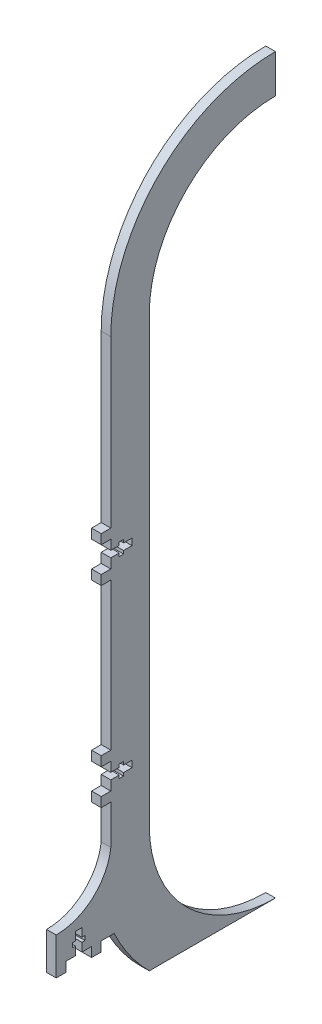
SolidWorks part; units mm, degrees
ref_plane "Front Plane" through (0, 0, 0) normal (0, 0, 1) x (1, 0, 0)
ref_plane "Top Plane" through (0, 0, 0) normal (0, 1, 0) x (1, 0, 0)
ref_plane "Right Plane" through (0, 0, 0) normal (1, 0, 0) x (0, 0, -1)
sketch "Elevator Ball Support Rail" plane through (0, 0, 0) normal (1, 0, 0) x (0, 0, -1)
  line L0 (83.312, 229.362) -> (83.312, 254.762)
  line L1 (-31.75, -120.142) -> (-25.4, -120.142)
  line L2 (83.312, -229.362) -> (0, -229.362)
  line L3 (-31.75, -196.342) -> (-23.2361, -196.342)
  line L6 (0, 146.05) -> (0, -146.05)
  line L7 (-25.4, -146.05) -> (-25.4, -196.342) construction
  line L8 (0, -146.05) -> (0, -229.362) construction
  line L12 (-61.468, -178.0893) -> (-61.468, -196.342)
  line L42 (0, 0) -> (-25.4, 0) construction
  line L46 (-25.4, 6.858) -> (-25.4, -90.424)
  line L47 (-25.4, -90.424) -> (-31.75, -90.424)
  line L48 (-25.4, -96.774) -> (-25.4, -103.124)
  line L49 (-31.75, -90.424) -> (-31.75, -96.774)
  line L50 (-31.75, -96.774) -> (-25.4, -96.774)
  line L51 (-25.4, -103.124) -> (-19.865, -103.124)
  line L52 (-19.865, -103.124) -> (-19.865, -101.083)
  line L53 (-19.865, -101.083) -> (-16.965, -101.083)
  line L54 (-16.965, -101.083) -> (-16.965, -103.124)
  line L55 (-16.965, -103.124) -> (-11.43, -103.124)
  line L56 (-11.43, -103.124) -> (-11.43, -107.442)
  line L57 (-11.43, -107.442) -> (-16.965, -107.442)
  line L58 (-16.965, -107.442) -> (-16.965, -109.483)
  line L59 (-16.965, -109.483) -> (-19.865, -109.483)
  line L60 (-19.865, -109.483) -> (-19.865, -107.442)
  line L61 (-19.865, -107.442) -> (-25.4, -107.442)
  line L62 (-25.4, -107.442) -> (-25.4, -113.792)
  line L63 (-25.4, -113.792) -> (-31.75, -113.792)
  line L64 (-31.75, -113.792) -> (-31.75, -120.142)
  line L66 (-25.4, -120.142) -> (-25.4, -146.05)
  line L68 (-25.4, 36.576) -> (-25.4, 146.05)
  arc A0 (0, 146.05) -> (83.312, 229.362) centre (83.312, 146.05) cw
  arc A1 (83.312, 254.762) -> (-25.4, 146.05) centre (83.312, 146.05) ccw
  arc A2 (0, -146.05) -> (83.312, -229.362) centre (83.312, -146.05) ccw
  arc A3 (-23.2361, -196.342) -> (0, -229.362) centre (83.312, -146.05) ccw
  arc A4 (-61.468, -178.0893) -> (-25.4, -146.05) centre (-61.468, -141.768) ccw
  point P4 (0, 0)
  line B0 (-55.118, -196.342) -> (-55.118, -202.692)
  line B1 (-55.118, -202.692) -> (-61.468, -202.692)
  line B2 (-61.468, -202.692) -> (-61.468, -196.342)
  line B3 (-48.768, -196.342) -> (-48.768, -190.807)
  line B4 (-48.768, -190.807) -> (-50.809, -190.807)
  line B5 (-50.809, -190.807) -> (-50.809, -187.907)
  line B6 (-50.809, -187.907) -> (-48.768, -187.907)
  line B7 (-48.768, -187.907) -> (-48.768, -182.372)
  line B8 (-48.768, -182.372) -> (-44.45, -182.372)
  line B9 (-44.45, -182.372) -> (-44.45, -187.907)
  line B10 (-44.45, -187.907) -> (-42.409, -187.907)
  line B11 (-42.409, -187.907) -> (-42.409, -190.807)
  line B12 (-42.409, -190.807) -> (-44.45, -190.807)
  line B13 (-44.45, -190.807) -> (-44.45, -196.342)
  line B14 (-46.609, -182.372) -> (-46.609, -196.342) construction
  line B15 (-38.1, -196.342) -> (-44.45, -196.342)
  line B16 (-31.75, -202.692) -> (-31.75, -196.342)
  line B17 (-55.118, -196.342) -> (-48.768, -196.342)
  line B18 (-38.1, -202.692) -> (-31.75, -202.692)
  line B19 (-38.1, -196.342) -> (-38.1, -202.692)
  line B20 (-25.4, 30.226) -> (-31.75, 30.226)
  line B21 (-31.75, 30.226) -> (-31.75, 36.576)
  line B22 (-31.75, 36.576) -> (-25.4, 36.576)
  line B23 (-25.4, 23.876) -> (-19.865, 23.876)
  line B24 (-19.865, 23.876) -> (-19.865, 25.917)
  line B25 (-19.865, 25.917) -> (-16.965, 25.917)
  line B26 (-16.965, 25.917) -> (-16.965, 23.876)
  line B27 (-16.965, 23.876) -> (-11.43, 23.876)
  line B28 (-11.43, 23.876) -> (-11.43, 19.558)
  line B29 (-11.43, 19.558) -> (-16.965, 19.558)
  line B30 (-16.965, 19.558) -> (-16.965, 17.517)
  line B31 (-16.965, 17.517) -> (-19.865, 17.517)
  line B32 (-19.865, 17.517) -> (-19.865, 19.558)
  line B33 (-19.865, 19.558) -> (-25.4, 19.558)
  line B34 (-11.43, 21.717) -> (-25.4, 21.717) construction
  line B35 (-25.4, 13.208) -> (-25.4, 19.558)
  line B36 (-31.75, 6.858) -> (-25.4, 6.858)
  line B37 (-25.4, 30.226) -> (-25.4, 23.876)
  line B38 (-31.75, 13.208) -> (-31.75, 6.858)
  line B39 (-25.4, 13.208) -> (-31.75, 13.208)
  dimension "D5" = 25.4
  dimension "D4" = 83.312
  dimension "D7" = 83.312
  dimension "D8" = 26.67
  dimension "D6" = 203.2
  dimension "D1" = 6.35
  dimension "D3" = 292.1
  dimension "D9" = 40.604
  dimension "D20" = 50.292
  dimension "D28" = 6.35
  dimension "D29" = 4.318
  dimension "D30" = 2.9
  dimension "D31" = 13.97
  dimension "D32" = 6.35
  dimension "D33" = 8.4
  dimension "D34" = 6.35
  dimension "D36" = 25.4
  dimension "D37" = 76.2
sketch_block_instance "Male T-slot assembly-1"
sketch_block "Male T-slot assembly" parameters "D1"=6.35, "D2"=6.35, "D3"=4.318, "D4"=2.9, "D5"=8.4, "D6"=13.97, "D7"=6.35
sketch_block_instance "Male T-slot assembly-5"
extrude "Boss-Extrude2" add sketch "Elevator Ball Support Rail" along normal blind 6.35
equation "\"Ball Diameter\"= 1.75in"
equation "\"Pulley Diameter\" = 1in"
equation "\"Reactor Height\" = 14in"
equation "\"Sheet Thickness\"= 0.25in"
equation "\"Screw Diameter\"= .17in"
equation "\"Robot Diameter\"= 14in"
equation "\"Castor Screw Diameter\"= 0.22in"
equation "\"Wheel Diameter\" = 4in"
equation "\"Nut Diameter\" = 8.4mm"
equation "\"Nut Height\" = 2.9mm"
equation "\"Screw Height\" = 0.55in"
equation "\"D11@Elevator Ball Support Rail\"=\"Sheet Thickness\""
equation "\"Elevator Height\" = 11.5in"
equation "\"D7@Elevator Ball Support Rail\" = \"Elevator Clearance from Axis\""
equation "\"D13@Elevator Ball Support Rail\"=\"Sheet Thickness\""
equation "\"D1@T-Slot\" = \"Screw Diameter\""
equation "\"D16@Elevator Ball Support Rail\"=\"Nut Diameter\""
equation "\"D15@Elevator Ball Support Rail\"=\"Nut Height\""
equation "\"D1@Boss-Extrude2\"=\"Sheet Thickness\""
equation "\"D3@Elevator Ball Support Rail\"=\"Elevator Height\""
equation "\"Elevator Width\" = \"Ball Diameter\" + 0.25in"
equation "\"Elevator Bearing Diameter\" = sqr(2*(\"Sheet Thickness\"^2)) + 0.2in"
equation "\"Elevator Axle Endcap Diameter\" = \"Pulley Diameter\" + 0.25in"
equation "\"Elevator Axle Length\" = \"Elevator Width\" + 8*\"Sheet Thickness\""
equation "\"Elevator Clearance from Axis\" = 3.28in"
equation "\"D4@Elevator Ball Support Rail\"=\"Elevator Clearance from Axis\""
equation "\"D32@Elevator Ball Support Rail\"=\"Sheet Thickness\""
equation "\"D33@Elevator Ball Support Rail\"=\"Nut Diameter\""
equation "\"D34@Elevator Ball Support Rail\"=\"Sheet Thickness\""
equation "\"D30@Elevator Ball Support Rail\"=\"Nut Height\""
equation "\"D28@Elevator Ball Support Rail\"=\"Sheet Thickness\""
equation "\"D29@Elevator Ball Support Rail\"=\"Screw Diameter\""
equation "\"D31@Elevator Ball Support Rail\" = \"Screw Height\""
equation "\"D1@Elevator Ball Support Rail\"=\"Sheet Thickness\""
equation "\"Ball Radius\" = \"Ball Diameter\"/2"
equation "\"Elevator Horizontal Clearance\" = \"Elevator Width\" + 0.5in"
equation "\"Claw Horizontal Seperation\" = (\"Elevator Width\"/2) - (1.5 * \"Sheet Thickness\") - 0.15in"
equation "\"Claw Radius\" = \"Ball Radius\" + 0.1in"
equation "\"Castor Wheel Height\" = 1.25in"
equation "\"D8@Elevator Ball Support Rail\"=\"Castor Wheel Height\"-0.2in"
